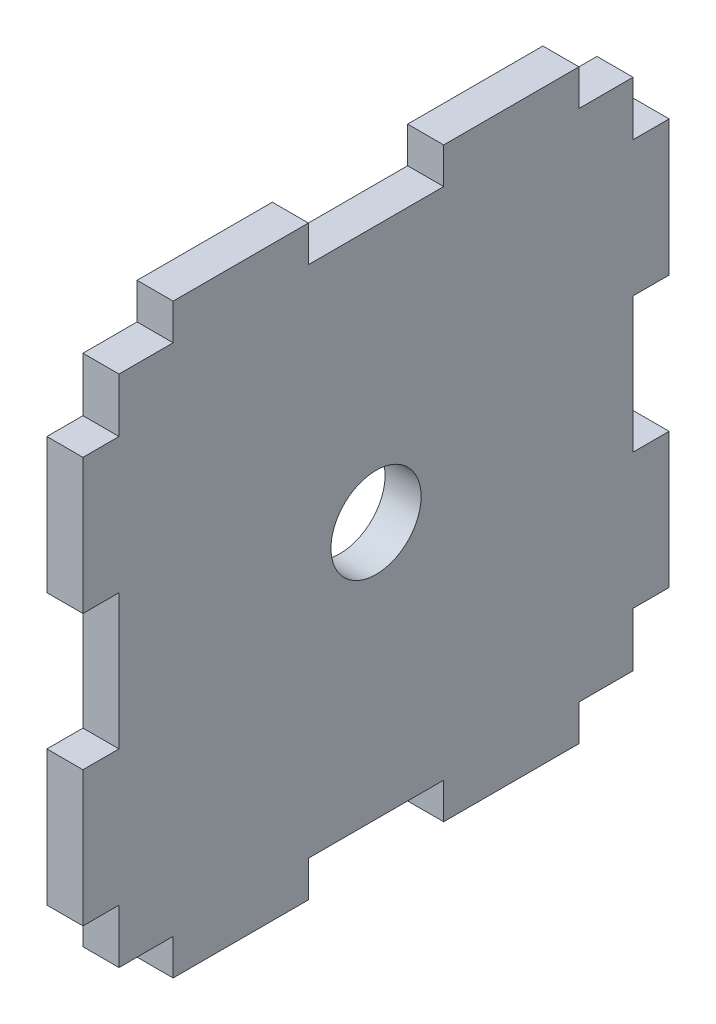
SolidWorks part; units mm, degrees
ref_plane "Front Plane" through (0, 0, 0) normal (0, 0, 1) x (1, 0, 0)
ref_plane "Top Plane" through (0, 0, 0) normal (0, 1, 0) x (1, 0, 0)
ref_plane "Right Plane" through (0, 0, 0) normal (1, 0, 0) x (0, 0, -1)
sketch "Sketch1" plane through (0, 0, 0) normal (1, 0, 0) x (0, 0, -1)
  line L1 (0, 0) -> (65, 0)
  line L2 (0, 0) -> (0, 65)
  line L3 (0, 65) -> (65, 65)
  line L4 (65, 0) -> (65, 65)
  dimension "D1" = 65
  dimension "D2" = 65
extrude "Boss-Extrude1" add sketch "Sketch1" along normal blind 4
sketch "Sketch2" plane through (4, 0, 0) normal (1, 0, 0) x (0, 0, -1)
  line L0 (0, 65) -> (65, 0) construction
  line L3 (17, 17) -> (17, 48) construction
  line L5 (48, 17) -> (48, 48) construction
  line L6 (17, 17) -> (48, 48) construction
  line L7 (17, 48) -> (48, 17) construction
  circle A1 centre (32.5, 32.5) radius 5
  point P4 (32.5, 32.5)
  dimension "D3" = 10
  dimension "D1" = 31
extrude "Cut-Extrude1" cut sketch "Sketch2" against normal blind 4
sketch "Sketch3" plane through (4, 0, 0) normal (1, 0, 0) x (0, 0, -1)
  line L0 (65, 65) -> (0, 65) construction
  line L1 (0, 65) -> (10, 65)
  line L2 (0, 65) -> (0, 61)
  line L3 (0, 61) -> (10, 61)
  line L4 (10, 65) -> (10, 61)
  line L5 (25, 65) -> (40, 65)
  line L6 (25, 65) -> (25, 61)
  line L7 (25, 61) -> (40, 61)
  line L8 (40, 65) -> (40, 61)
  line L9 (27.5, 32.5) -> (32.5, 32.5) construction
  line L10 (65, 65) -> (55, 65)
  line L11 (65, 65) -> (65, 61)
  line L12 (65, 61) -> (55, 61)
  line L13 (55, 65) -> (55, 61)
  line L14 (55, 0) -> (55, 4)
  line L15 (65, 4) -> (55, 4)
  line L16 (65, 0) -> (65, 4)
  line L17 (65, 0) -> (55, 0)
  line L18 (40, 0) -> (40, 4)
  line L19 (25, 4) -> (40, 4)
  line L20 (25, 0) -> (25, 4)
  line L21 (25, 0) -> (40, 0)
  line L22 (10, 0) -> (10, 4)
  line L23 (0, 4) -> (10, 4)
  line L24 (0, 0) -> (0, 4)
  line L25 (0, 0) -> (10, 0)
  circle A0 centre (32.5, 32.5) radius 5 construction
  dimension "D1" = 15
  dimension "D2" = 15
  dimension "D3" = 10
  dimension "D4" = 10
  dimension "D5" = 4
  dimension "D6" = 4
  dimension "D7" = 4
extrude "Cut-Extrude2" cut sketch "Sketch3" against normal blind 4
sketch "Sketch5" plane through (4, 0, 0) normal (1, 0, 0) x (0, 0, -1)
  line L0 (0, 61) -> (0, 4) construction
  line L1 (0, 61) -> (4, 61)
  line L2 (0, 61) -> (0, 55)
  line L3 (0, 55) -> (4, 55)
  line L4 (4, 61) -> (4, 55)
  line L5 (4, 40) -> (0, 40)
  line L6 (4, 40) -> (4, 25)
  line L7 (4, 25) -> (0, 25)
  line L8 (0, 40) -> (0, 25)
  line L9 (10, 4) -> (0, 4) construction
  line L10 (0, 10) -> (4, 10)
  line L11 (0, 10) -> (0, 4)
  line L12 (0, 4) -> (4, 4)
  line L13 (4, 10) -> (4, 4)
  line L14 (32.5, 4) -> (32.5, 55.5153) construction
  line L15 (40, 4) -> (25, 4) construction
  line L16 (61, 10) -> (61, 4)
  line L17 (65, 4) -> (61, 4)
  line L18 (65, 10) -> (65, 4)
  line L19 (65, 10) -> (61, 10)
  line L20 (65, 40) -> (65, 25)
  line L21 (61, 25) -> (65, 25)
  line L22 (61, 40) -> (61, 25)
  line L23 (61, 40) -> (65, 40)
  line L24 (61, 61) -> (61, 55)
  line L25 (65, 55) -> (61, 55)
  line L26 (65, 61) -> (65, 55)
  line L27 (65, 61) -> (61, 61)
  point P17 (2, 25)
  dimension "D1" = 4
  dimension "D2" = 4
  dimension "D3" = 4
  dimension "D4" = 15
  dimension "D5" = 15
  dimension "D6" = 6
  dimension "D7" = 6
extrude "Cut-Extrude3" cut sketch "Sketch5" against normal blind 4
